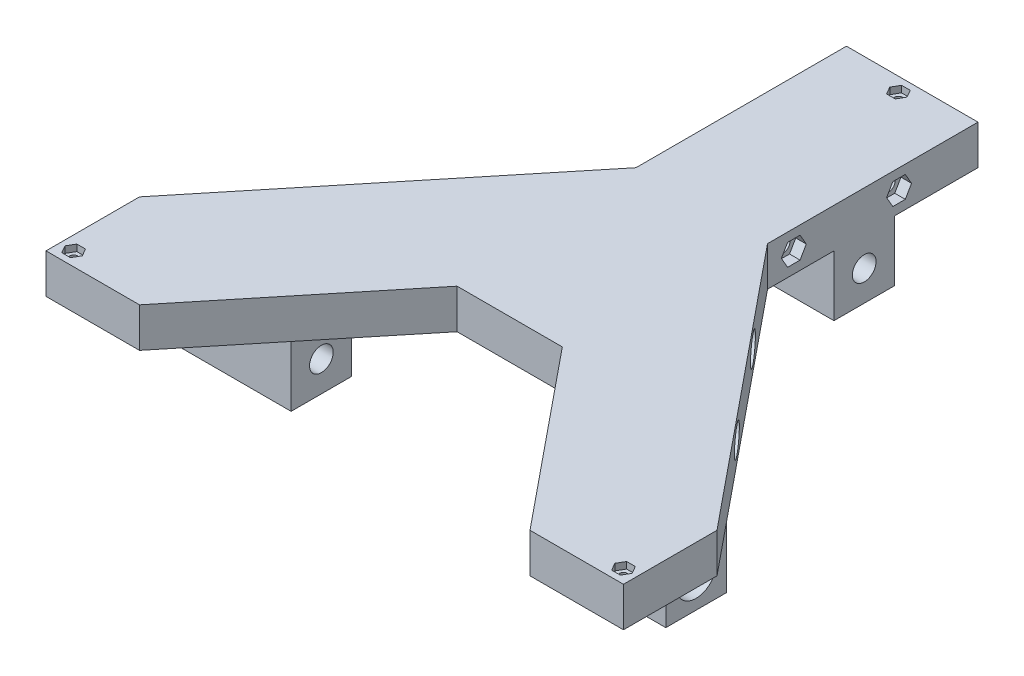
SolidWorks part; units mm, degrees
ref_plane "Front Plane" through (0, 0, 0) normal (0, 0, 1) x (1, 0, 0)
ref_plane "Top Plane" through (0, 0, 0) normal (0, 1, 0) x (1, 0, 0)
ref_plane "Right Plane" through (0, 0, 0) normal (1, 0, 0) x (0, 0, -1)
sketch "Sketch1" plane through (0, 0, 0) normal (0, 1, 0) x (1, 0, 0)
  line L0 (0, 0) -> (0, 143741.8209) construction
  line L1 (25, 0) -> (-25, 0)
  line L2 (-25, 0) -> (-25, -80)
  line L3 (25, 0) -> (25, -80)
  line L4 (-25, -80) -> (-109.75, -183.9619)
  line L5 (25, -80) -> (109.75, -183.9619)
  line L6 (-109.75, -183.9619) -> (-109.75, -219.5)
  line L7 (109.75, -183.9619) -> (109.75, -219.5)
  line L8 (-109.75, -219.5) -> (-74.2119, -219.5)
  line L9 (109.75, -219.5) -> (74.2119, -219.5)
  line L10 (-74.2119, -219.5) -> (-20, -152.9988)
  line L11 (74.2119, -219.5) -> (20, -152.9988)
  line L12 (-20, -152.9988) -> (20, -152.9988)
  point P6 (0, 0)
  point P16 (0, -152.9988)
  dimension "D1" = 219.5
  dimension "D2" = 219.5
  dimension "D3" = 50
  dimension "D4" = 50
  dimension "D5" = 80
  dimension "D6" = 40
extrude "Boss-Extrude1" add sketch "Sketch1" along normal blind 15
sketch "Sketch4" plane through (-109.75, 0, 0) normal (-1, 0, 0) x (0, 0, 1)
  line L0 (0, 15) -> (0, 0) construction
  line L1 (80, 15) -> (80, 0) construction
  line L2 (152.9988, 15) -> (152.9988, 0) construction
  circle A0 centre (30, 7.5) radius 2.55
  circle A1 centre (70, 7.5) radius 2.55
  circle A2 centre (110, 7.5) radius 2.55
  circle A3 centre (142.9988, 7.5) radius 2.55
  point P10 (0, 7.5)
  dimension "D1" = 5.1
  dimension "D2" = 30
  dimension "D3" = 10
  dimension "D4" = 30
  dimension "D5" = 10
extrude "Cut-Extrude1" cut sketch "Sketch4" against normal through all
sketch "Sketch5" plane through (-25, 0, 0) normal (-1, 0, 0) x (0, 0, 1)
  circle A0 centre (30, 7.5) radius 4.5
  circle A1 centre (70, 7.5) radius 4.5
  circle A2 centre (110, 7.5) radius 4.5
  circle A3 centre (142.9988, 7.5) radius 4.5
  dimension "D1" = 9
extrude "Cut-Extrude3" cut sketch "Sketch5" against normal blind 3.5 and the other way through all
sketch "Sketch6" plane through (25, 0, 0) normal (1, 0, 0) x (0, 0, -1)
  circle A0 centre (-142.9988, 7.5) radius 5
  circle A1 centre (-110, 7.5) radius 5
  dimension "D1" = 10
  dimension "D2" = 10
extrude "Cut-Extrude4" cut sketch "Sketch6" along normal through all
sketch "Sketch7" plane through (25, 0, 0) normal (1, 0, 0) x (0, 0, -1)
  line L1 (-34.7343, 7.5) -> (-32.3671, 3.4)
  line L2 (-32.3671, 3.4) -> (-27.6329, 3.4)
  line L3 (-27.6329, 3.4) -> (-25.2657, 7.5)
  line L4 (-25.2657, 7.5) -> (-27.6329, 11.6)
  line L5 (-27.6329, 11.6) -> (-32.3671, 11.6)
  line L6 (-32.3671, 11.6) -> (-34.7343, 7.5)
  line L7 (-74.7343, 7.5) -> (-72.3671, 3.4)
  line L8 (-72.3671, 3.4) -> (-67.6329, 3.4)
  line L9 (-67.6329, 3.4) -> (-65.2657, 7.5)
  line L10 (-65.2657, 7.5) -> (-67.6329, 11.6)
  line L11 (-67.6329, 11.6) -> (-72.3671, 11.6)
  line L12 (-72.3671, 11.6) -> (-74.7343, 7.5)
  line L13 (-114.7343, 7.5) -> (-112.3671, 3.4)
  line L14 (-112.3671, 3.4) -> (-107.6329, 3.4)
  line L15 (-107.6329, 3.4) -> (-105.2657, 7.5)
  line L16 (-105.2657, 7.5) -> (-107.6329, 11.6)
  line L17 (-107.6329, 11.6) -> (-112.3671, 11.6)
  line L18 (-112.3671, 11.6) -> (-114.7343, 7.5)
  line L19 (-147.7331, 7.5) -> (-145.366, 3.4)
  line L20 (-145.366, 3.4) -> (-140.6317, 3.4)
  line L21 (-140.6317, 3.4) -> (-138.2646, 7.5)
  line L22 (-138.2646, 7.5) -> (-140.6317, 11.6)
  line L23 (-140.6317, 11.6) -> (-145.366, 11.6)
  line L24 (-145.366, 11.6) -> (-147.7331, 7.5)
  circle A0 centre (-30, 7.5) radius 4.1 construction
  circle A1 centre (-70, 7.5) radius 4.1 construction
  circle A2 centre (-110, 7.5) radius 4.1 construction
  circle A3 centre (-142.9988, 7.5) radius 4.1 construction
  dimension "D1" = 8.2
extrude "Cut-Extrude5" cut sketch "Sketch7" against normal blind 4
sketch "Sketch8" plane through (0, 15, 0) normal (0, 1, 0) x (1, 0, 0)
  line L0 (25, 0) -> (-25, 0) construction
  line L1 (-109.75, -219.5) -> (-74.2119, -219.5) construction
  line L3 (-109.75, -183.9619) -> (-109.75, -219.5) construction
  line L4 (109.75, -219.5) -> (109.75, -183.9619) construction
  circle A0 centre (0, -5.25) radius 1.6
  circle A1 centre (-104.5, -214.25) radius 1.6
  circle A2 centre (104.5, -214.25) radius 1.6
  dimension "D1" = 3.2
  dimension "D3" = 5.25
  dimension "D2" = 5.25
  dimension "D4" = 5.25
  dimension "D5" = 5.25
extrude "Cut-Extrude6" cut sketch "Sketch8" against normal through all
sketch "Sketch9" plane through (0, 15, 0) normal (0, 1, 0) x (1, 0, 0)
  line L1 (-101.2091, -214.25) -> (-102.8546, -211.4)
  line L2 (-102.8546, -211.4) -> (-106.1454, -211.4)
  line L3 (-106.1454, -211.4) -> (-107.7909, -214.25)
  line L4 (-107.7909, -214.25) -> (-106.1454, -217.1)
  line L5 (-106.1454, -217.1) -> (-102.8546, -217.1)
  line L6 (-102.8546, -217.1) -> (-101.2091, -214.25)
  line L7 (101.2091, -214.25) -> (102.8546, -217.1)
  line L8 (102.8546, -217.1) -> (106.1454, -217.1)
  line L9 (106.1454, -217.1) -> (107.7909, -214.25)
  line L10 (107.7909, -214.25) -> (106.1454, -211.4)
  line L11 (106.1454, -211.4) -> (102.8546, -211.4)
  line L12 (102.8546, -211.4) -> (101.2091, -214.25)
  line L13 (3.2909, -5.25) -> (1.6454, -2.4)
  line L14 (1.6454, -2.4) -> (-1.6454, -2.4)
  line L15 (-1.6454, -2.4) -> (-3.2909, -5.25)
  line L16 (-3.2909, -5.25) -> (-1.6454, -8.1)
  line L17 (-1.6454, -8.1) -> (1.6454, -8.1)
  line L18 (1.6454, -8.1) -> (3.2909, -5.25)
  circle A0 centre (-104.5, -214.25) radius 2.85 construction
  circle A1 centre (104.5, -214.25) radius 2.85 construction
  circle A2 centre (0, -5.25) radius 2.85 construction
  dimension "D1" = 5.7
  dimension "D2" = 5.7
  dimension "D3" = 5.7
extrude "Cut-Extrude7" cut sketch "Sketch9" against normal blind 2.5
sketch "Sketch10" plane through (0, 0, 0) normal (0, -1, 0) x (1, 0, 0)
  line L0 (6.2244, 43.25) -> (-49993.7756, 43.25) construction
  line L1 (84.4314, 176.25) -> (-49915.5686, 176.25) construction
  line L2 (7.3106, 39.25) -> (-49992.6894, 39.25) construction
  line L3 (6.2244, 47.25) -> (-49993.7756, 47.25) construction
  line L4 (138.9608, 172.25) -> (-49932.948, 172.25) construction
  line L5 (77.9141, 180.25) -> (-49922.0859, 180.25) construction
  line L6 (25, 0) -> (-25, 0) construction
  line L7 (74.2119, 219.5) -> (109.75, 219.5) construction
  line L8 (-25, 0) -> (-25, 80) construction
  line L9 (25, 54.75) -> (-25, 54.75)
  line L10 (25, 54.75) -> (25, 31.75)
  line L11 (25, 31.75) -> (-25, 31.75)
  line L12 (-25, 54.75) -> (-25, 31.75)
  line L13 (25, 54.75) -> (-25, 31.75) construction
  line L14 (25, 31.75) -> (-25, 54.75) construction
  line L15 (25, 80) -> (25, 0) construction
  line L16 (94.0884, 164.75) -> (48.3292, 164.75)
  line L17 (109.75, 183.9619) -> (25, 80) construction
  line L18 (20, 152.9988) -> (74.2119, 219.5) construction
  line L20 (48.3292, 187.75) -> (94.0884, 187.75)
  line L24 (0, 0) -> (0, -50000) construction
  line L26 (-48.3292, 187.75) -> (-94.0884, 187.75)
  line L28 (-94.0884, 164.75) -> (-48.3292, 164.75)
  line L30 (-94.0884, 164.75) -> (-94.0884, 187.75)
  line L31 (-48.3292, 187.75) -> (-48.3292, 164.75)
  line L32 (48.3292, 187.75) -> (48.3292, 164.75)
  line L33 (94.0884, 164.75) -> (94.0884, 187.75)
  point P16 (0, 43.25)
  dimension "D1" = 43.25
  dimension "D2" = 43.25
  dimension "D3" = 4
  dimension "D4" = 4
  dimension "D5" = 4
  dimension "D6" = 4
  dimension "D7" = 23
  dimension "D8" = 23
  dimension "D9" = 11.5
  dimension "D10" = 23
extrude "Boss-Extrude2" add sketch "Sketch10" along normal blind 23
ref_plane "Plane1" through (-94.0884, 0, 0) normal (-1, 0, 0) x (0, 0, 1)
sketch "Sketch11" plane through (-94.0884, 0, 0) normal (-1, 0, 0) x (0, 0, 1)
  line L2 (164.75, -23) -> (164.75, 0) construction
  line L3 (187.75, -23) -> (164.75, -23) construction
  circle A0 centre (176.25, -11.5) radius 7.6
  dimension "D2" = 11.5
  dimension "D3" = 15.2
  dimension "D1" = 11.5
extrude "Cut-Extrude8" cut sketch "Sketch11" against normal blind 24 and the other way through all
sketch "Sketch12" plane through (-94.0884, 0, 0) normal (-1, 0, 0) x (0, 0, 1)
  circle A0 centre (176.25, -11.5) radius 4.5
  dimension "D1" = 9
extrude "Cut-Extrude9" cut sketch "Sketch12" against normal through all
mirror "Mirror1" about plane through (0, 0, 0) normal (1, 0, 0) of "Cut-Extrude8"
sketch "Sketch13" plane through (-25, 0, 0) normal (-1, 0, 0) x (0, 0, 1)
  line L0 (54.75, -23) -> (31.75, -23) construction
  line L1 (31.75, -23) -> (31.75, 0) construction
  circle A0 centre (43.25, -11.5) radius 4.5
  dimension "D1" = 9
  dimension "D2" = 11.5
  dimension "D3" = 11.5
extrude "Cut-Extrude10" cut sketch "Sketch13" against normal through all
sketch "Sketch14" plane through (0, 0, 0) normal (1, 0, 0) x (0, 0, -1)
  circle A0 centre (-43.25, -11.5) radius 7.6
  dimension "D1" = 15.2
extrude "Cut-Extrude11" cut sketch "Sketch14" against normal blind 12.5 and the other way blind 12.5 contours A0
sketch "Sketch16" plane through (0, 15, 0) normal (0, 1, 0) x (1, 0, 0)
  line L0 (-25, -19.5) -> (-8.4, -19.5)
  line L1 (-25, 0) -> (-25, -80) construction
  line L2 (-8.4, -19.5) -> (-8.4, -87.55)
  line L3 (-8.4, -87.55) -> (8.4, -87.55)
  line L4 (8.4, -87.55) -> (8.4, -19.5)
  line L5 (8.4, -19.5) -> (25, -19.5)
  line L6 (25, -80) -> (25, 0) construction
  line L7 (0, -87.55) -> (0, -152.9988)
  line L8 (-20, -152.9988) -> (20, -152.9988) construction
  line L9 (-21.5, -72.55) -> (21, -72.55) construction
  line L10 (74.2119, -219.5) -> (109.75, -219.5) construction
  point P14 (0, -152.9988)
  dimension "D1" = 15
  dimension "D2" = 200
  dimension "D3" = 16.6
